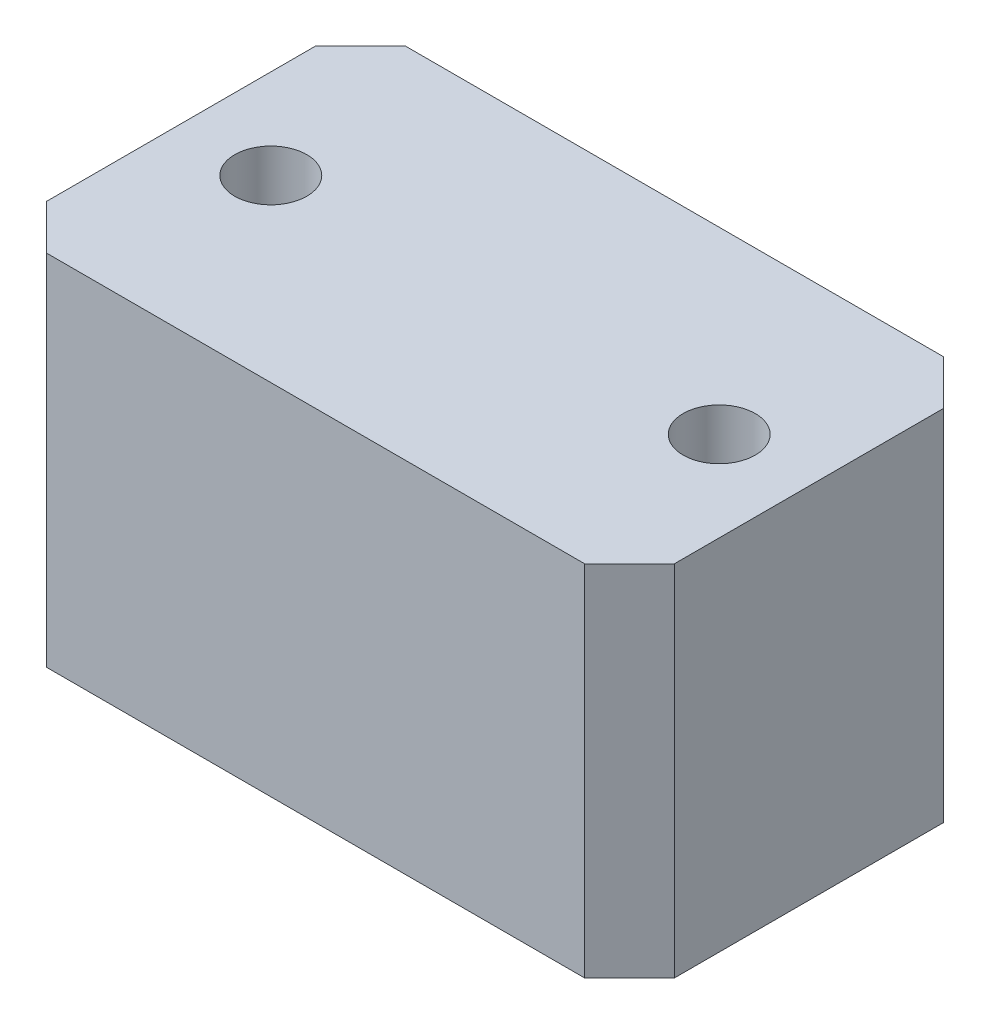
SolidWorks part; units mm, degrees
ref_plane "Front" through (0, 0, 0) normal (0, 0, 1) x (1, 0, 0)
ref_plane "Top" through (0, 0, 0) normal (0, 1, 0) x (1, 0, 0)
ref_plane "Right" through (0, 0, 0) normal (1, 0, 0) x (0, 0, -1)
sketch "Sketch1" plane through (0, 0, 0) normal (0, 1, 0) x (1, 0, 0)
  line L1 (-22.225, 12.7) -> (22.225, 12.7)
  line L2 (-22.225, 12.7) -> (-22.225, -12.7)
  line L3 (-22.225, -12.7) -> (22.225, -12.7)
  line L4 (22.225, 12.7) -> (22.225, -12.7)
  line L5 (-22.225, 12.7) -> (22.225, -12.7) construction
  line L6 (-22.225, -12.7) -> (22.225, 12.7) construction
  point P0 (0, 0)
  dimension "D1" = 25.4
  dimension "D2" = 44.45
extrude "Boss-Extrude1" add sketch "Sketch1" along normal blind 25.4
hole_wizard "#10 Clearance Hole1" positions "Sketch2" profile "Sketch3" hole size "#10" standard "ANSI Inch" end condition through all
sketch "Sketch2" plane through (0, 25.4, 0) normal (0, 1, 0) x (1, 0, 0)
  line L0 (0, 0) -> (-15.875, 0) construction
  line L1 (0, 0) -> (15.875, 0) construction
  line L2 (-22.225, 12.7) -> (-22.225, -12.7) construction
  point P0 (-15.875, 0)
  point P2 (15.875, 0)
  dimension "D1" = 6.35
sketch "Sketch3" plane through (-15.875, 25.4, 0) normal (1, 0, 0) x (0, 0, 1)
  line L0 (0, 0) -> (0, 25.4)
  line L1 (0, 25.4) -> (2.5527, 25.4)
  line L2 (2.5527, 25.4) -> (2.5527, 0)
  line L5 (2.5527, 0) -> (0, 0)
  line L11 (0, -6.35) -> (0, 107.95) construction
  dimension "Thru Hole Dia." = 5.1054
  dimension "Thru Hole Depth" = 25.4
chamfer "Chamfer1" distance 3.175 angle 45 4 edges at (-22.225, 12.7, -12.7) (-22.225, 12.7, 12.7) (22.225, 12.7, -12.7) (22.225, 12.7, 12.7)
